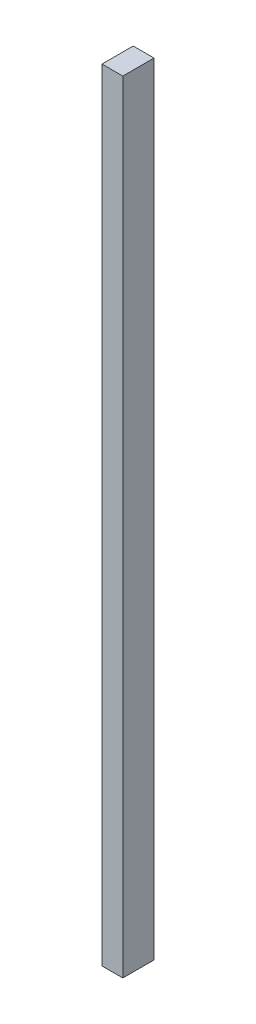
SolidWorks part; units mm, degrees
ref_plane "Front Plane" through (0, 0, 0) normal (0, 0, 1) x (1, 0, 0)
ref_plane "Top Plane" through (0, 0, 0) normal (0, 1, 0) x (1, 0, 0)
ref_plane "Right Plane" through (0, 0, 0) normal (1, 0, 0) x (0, 0, -1)
sketch "Sketch1" plane through (0, 0, 0) normal (0, 1, 0) x (1, 0, 0)
  line L1 (-4, -6) -> (4, -6)
  line L2 (-4, -6) -> (-4, 6)
  line L3 (-4, 6) -> (4, 6)
  line L4 (4, -6) -> (4, 6)
  line L5 (-4, -6) -> (4, 6) construction
  line L6 (-4, 6) -> (4, -6) construction
  point P0 (0, 0)
  dimension "D1" = 8
  dimension "D2" = 12
extrude "Boss-Extrude1" add sketch "Sketch1" along normal blind 300
